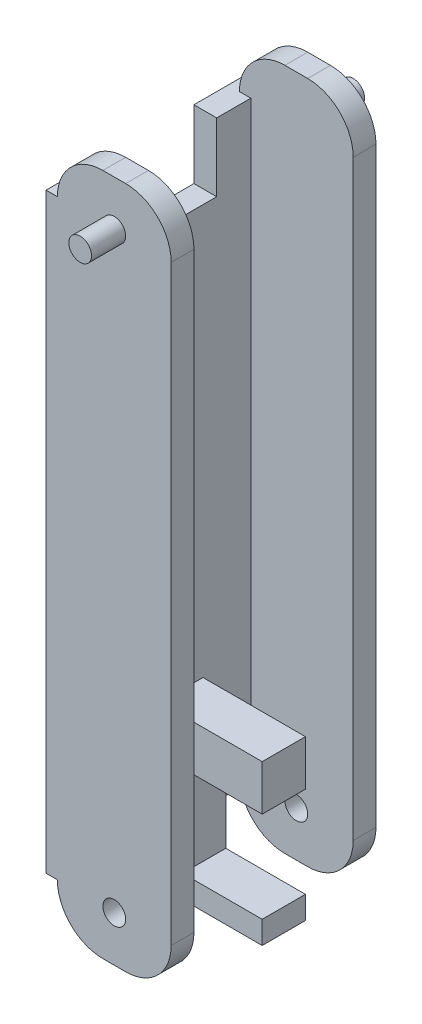
SolidWorks part; units mm, degrees
ref_plane "Front Plane" through (0, 0, 0) normal (0, 0, 1) x (1, 0, 0)
ref_plane "Top Plane" through (0, 0, 0) normal (0, 1, 0) x (1, 0, 0)
ref_plane "Right Plane" through (0, 0, 0) normal (1, 0, 0) x (0, 0, -1)
sketch "Sketch1" plane through (0, 0, 0) normal (0, 0, 1) x (1, 0, 0)
  line L0 (0, 7.8092) -> (0, -7.5836) construction
  line L1 (-16.5434, 0) -> (17.7066, 0) construction
  line L2 (-5, -20) -> (5, -20)
  line L6 (0, 7.8092) -> (0, 18.1168) construction
  line L7 (-25, 0) -> (-25, 260)
  line L8 (-5, 280) -> (5, 280)
  line L9 (25, 260) -> (25, 0)
  line L10 (0, 332.7621) -> (0, -24.8778) construction
  arc A0 (5, -20) -> (25, 0) centre (5, 0) ccw
  arc A1 (-5, -20) -> (-25, 0) centre (-5, 0) cw
  circle A2 centre (0, 0) radius 5
  arc A3 (5, 280) -> (25, 260) centre (5, 260) cw
  arc A4 (-25, 260) -> (-5, 280) centre (-5, 260) cw
  point P14 (25, -20)
  point P17 (-25, -20)
  point P22 (25, 280)
  dimension "D4" = 20
  dimension "D5" = 20
  dimension "D6" = 20
  dimension "D1" = 50
  dimension "D2" = 25
  dimension "D3" = 300
extrude "Boss-Extrude1" add sketch "Sketch1" along normal blind 10
sketch "Sketch2" plane through (0, 0, 10) normal (0, 0, 1) x (1, 0, 0)
  line L0 (0, 310.2932) -> (0, -54.3198) construction
  line L1 (5, 280) -> (-5, 280) construction
  circle A1 centre (0, 260) radius 5
  dimension "D1" = 20
  dimension "D2" = 10
extrude "Boss-Extrude2" add sketch "Sketch2" along normal blind 15
sketch "Sketch3" plane through (0, 0, 0) normal (0, 0, -1) x (-1, 0, 0)
  line L0 (0, -108.7365) -> (0, 392.6868) construction
  line L1 (25, 0) -> (20, 0)
  line L2 (20, 0) -> (20, 260)
  line L3 (20, 260) -> (25, 260)
  line L4 (25, 260) -> (25, 0)
  dimension "D1" = 260
  dimension "D2" = 260
  dimension "D3" = 5
  dimension "D4" = 20
extrude "Boss-Extrude3" add sketch "Sketch3" along normal blind 35
mirror "Mirror1" about plane through (0, 0, -35) normal (0, 0, 1) of "Boss-Extrude3", "Boss-Extrude2", "Boss-Extrude1"
sketch "Sketch8" plane through (0, 0, 0) normal (0, -1, 0) x (1, 0, 0)
  line L0 (-25, -30) -> (-20, -30)
  line L2 (-25, -70) -> (-25, 0) construction
  line L3 (-20, -70) -> (-20, 0) construction
  line L4 (-20, -30) -> (-20, -49)
  line L5 (-20, -49) -> (-25, -49)
  line L6 (-25, -49) -> (-25, -30)
  line L7 (-20, 0) -> (-25, 0) construction
  line L8 (-5, -70) -> (-25, -70) construction
  dimension "D1" = 30
  dimension "D2" = 19
  dimension "D3" = 21
extrude "Boss-Extrude4" add sketch "Sketch8" along normal blind 20
sketch "Sketch9" plane through (-20, 0, 0) normal (1, 0, 0) x (0, 0, -1)
  line L0 (30, -20) -> (30, -10)
  line L1 (30, -20) -> (30, 0) construction
  line L2 (30, -10) -> (49, -10)
  line L3 (49, -20) -> (49, 0) construction
  line L4 (49, -10) -> (49, -20)
  line L5 (49, -20) -> (30, -20)
  line L6 (30, 286.5383) -> (30, -36.1632) construction
  line L7 (49, 286.5383) -> (49, -36.1632) construction
  line L8 (49, 30) -> (30, 30)
  line L9 (30, 30) -> (30, 50)
  line L10 (30, 50) -> (49, 50)
  line L11 (49, 50) -> (49, 30)
  dimension "D1" = 10
  dimension "D2" = 40
  dimension "D3" = 20
extrude "Boss-Extrude5" add sketch "Sketch9" along normal blind 45
sketch "Sketch10" plane through (-20, 0, 0) normal (1, 0, 0) x (0, 0, -1)
  line L0 (30, 30) -> (30, -10)
  line L1 (30, -10) -> (49, -10)
  line L2 (49, -10) -> (49, 30)
  line L3 (49, 30) -> (30, 30)
extrude "Boss-Extrude6" add sketch "Sketch10" along normal blind 10
sketch "Sketch11" plane through (-25, 0, 0) normal (-1, 0, 0) x (0, 0, 1)
  line L0 (10, 0) -> (-30, 0)
  line L1 (-30, 0) -> (-30, -20)
  line L2 (-30, -20) -> (-49, -20)
  line L3 (-49, -20) -> (-49, 0)
  line L4 (-49, 0) -> (-80, 0)
  line L5 (-80, 0) -> (-80, 260)
  line L6 (-80, 265) -> (-80, 255) construction
  line L7 (-80, 260) -> (10, 260)
  line L8 (10, 260) -> (10, 0)
extrude "Boss-Extrude7" add sketch "Sketch11" along normal blind 5
sketch "Sketch12" plane through (-30, 0, 0) normal (-1, 0, 0) x (0, 0, 1)
  line L0 (-55, 260) -> (-55, 230)
  line L1 (10, 260) -> (-80, 260) construction
  line L2 (-55, 230) -> (-15, 230)
  line L3 (-15, 230) -> (-15, 260)
  line L4 (-15, 260) -> (-55, 260)
  line L5 (10, 0) -> (10, 260) construction
  line L6 (-80, 260) -> (-80, 0) construction
  dimension "D1" = 25
  dimension "D2" = 25
  dimension "D3" = 30
extrude "Cut-Extrude1" cut sketch "Sketch12" against normal blind 10
